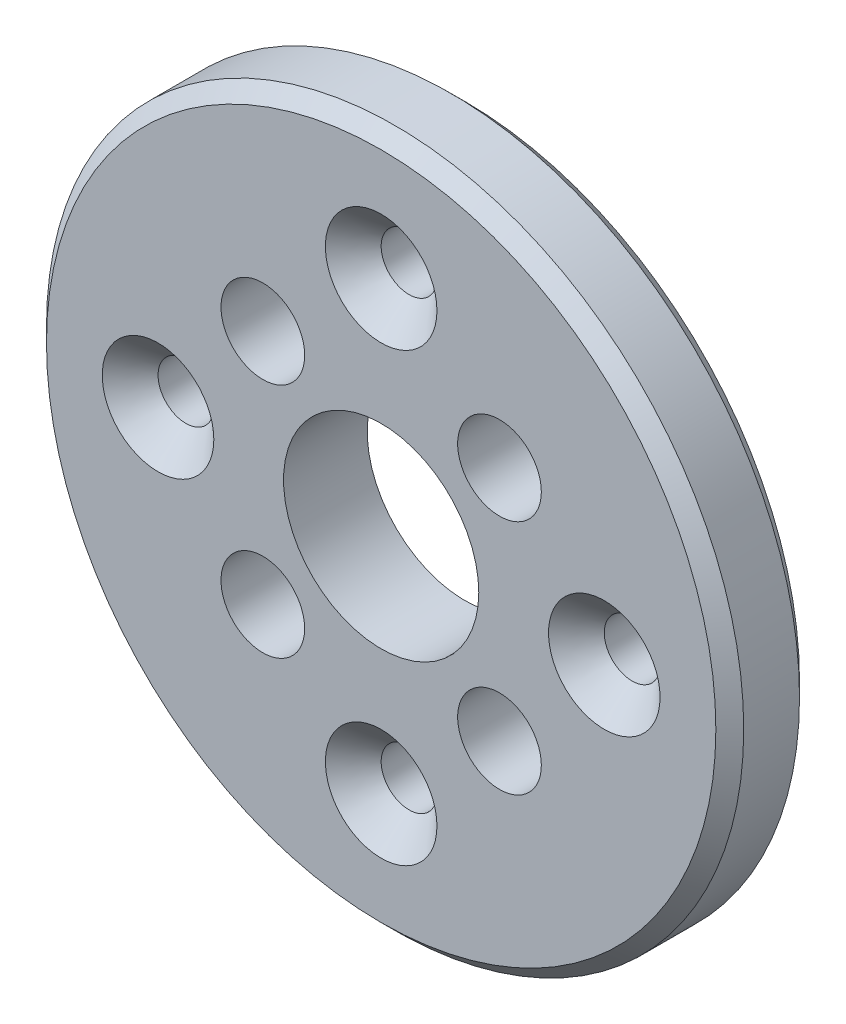
SolidWorks part; units mm, degrees
ref_plane "前视基准面" through (0, 0, 0) normal (0, 0, 1) x (1, 0, 0)
ref_plane "上视基准面" through (0, 0, 0) normal (0, 1, 0) x (1, 0, 0)
ref_plane "右视基准面" through (0, 0, 0) normal (1, 0, 0) x (0, 0, -1)
sketch "草图1" plane through (0, 0, 0) normal (0, 0, 1) x (1, 0, 0)
  line L0 (0, 11.6117) -> (0, -11.0994) construction
  line L1 (-7.1658, -7.1658) -> (7.309, 7.309) construction
  line L2 (-7.1513, 7.1513) -> (5.9182, -5.9182) construction
  circle A1 centre (0, 0) radius 8 construction
  circle A2 centre (0, 8) radius 1
  circle A3 centre (8, 0) radius 1
  circle A4 centre (0, -8) radius 1
  circle A5 centre (-8, 0) radius 1
  circle A6 centre (0, 0) radius 12.5
  circle A8 centre (-4.2426, 4.2426) radius 1.5
  circle A9 centre (0, 0) radius 3.5
  circle A10 centre (4.2426, 4.2426) radius 1.5
  circle A11 centre (4.2426, -4.2426) radius 1.5
  circle A12 centre (-4.2426, -4.2426) radius 1.5
  point P17 (0, 0)
  point P31 (0, 0)
  dimension "D2" = 16
  dimension "D3" = 2
  dimension "D5" = 25
  dimension "D7" = 7
  dimension "D8" = 3
  dimension "D9" = 6
  dimension "D4" = 4
extrude "凸台-拉伸1" add sketch "草图1" along normal mid plane 3
chamfer "倒角2" distance 1 angle 45 4 edges at (9, 0, 1.5) (1, -8, 1.5) (-7, 0, 1.5) (1, 8, 1.5)
chamfer "倒角1" distance 0.5 angle 45 2 edges at (12.5, 0, -1.5) (12.5, 0, 1.5)
